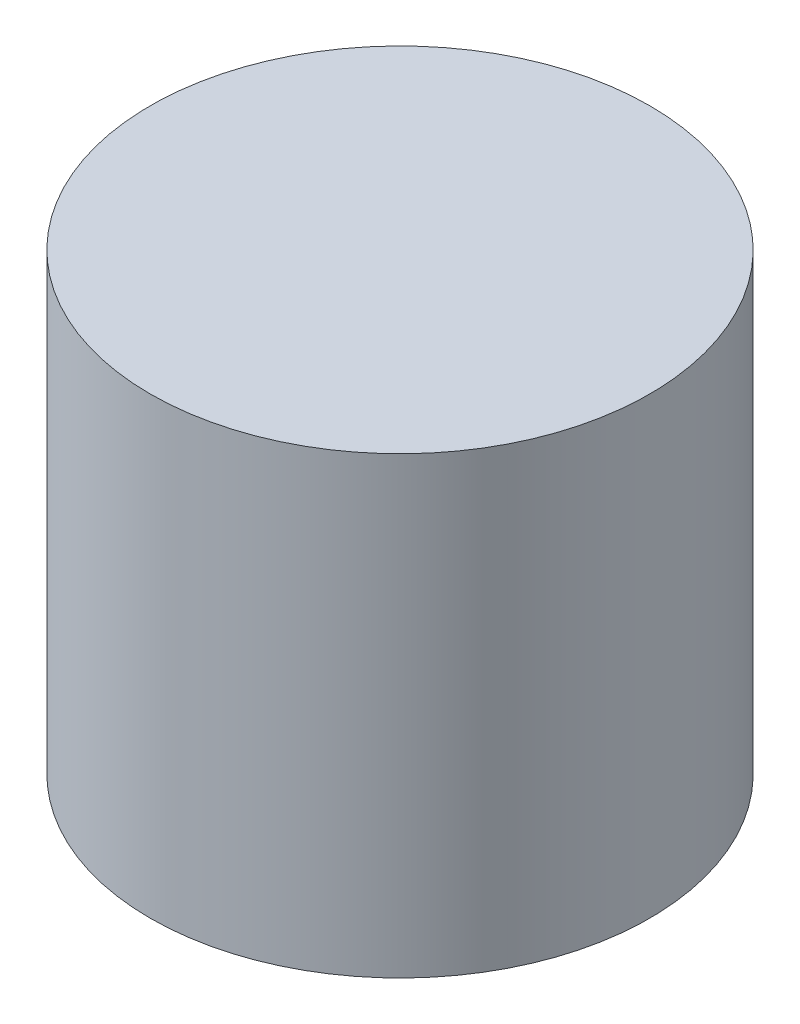
SolidWorks part; units mm, degrees
ref_plane "Front Plane" through (0, 0, 0) normal (0, 0, 1) x (1, 0, 0)
ref_plane "Top Plane" through (0, 0, 0) normal (0, 1, 0) x (1, 0, 0)
ref_plane "Right Plane" through (0, 0, 0) normal (1, 0, 0) x (0, 0, -1)
sketch "Sketch1" plane through (0, 0, 0) normal (0, 1, 0) x (1, 0, 0)
  circle A0 centre (0, 0) radius 11
  dimension "D1" = 22
extrude "Boss-Extrude1" add sketch "Sketch1" along normal blind 20
